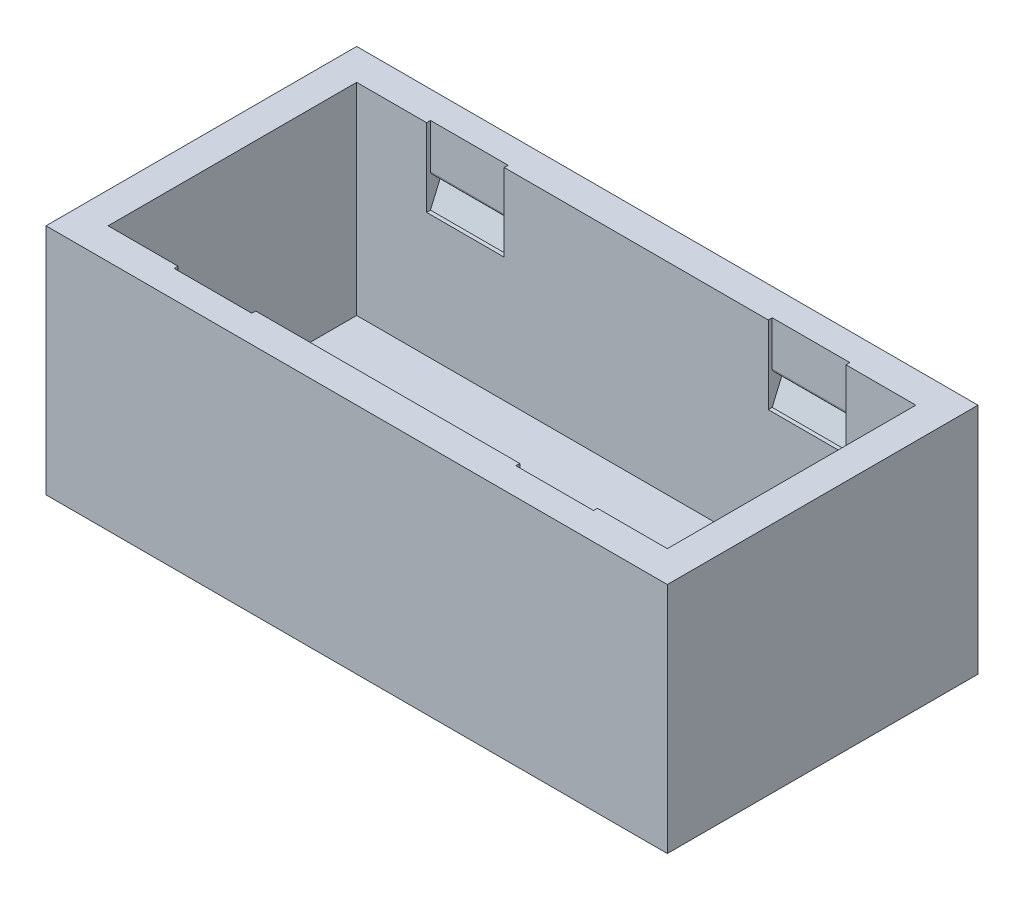
SolidWorks part; units mm, degrees
ref_plane "Front Plane" through (0, 0, 0) normal (0, 0, 1) x (1, 0, 0)
ref_plane "Top Plane" through (0, 0, 0) normal (0, 1, 0) x (1, 0, 0)
ref_plane "Right Plane" through (0, 0, 0) normal (1, 0, 0) x (0, 0, -1)
sketch "Sketch1" plane through (0, 0, 0) normal (0, 1, 0) x (1, 0, 0)
  line L1 (-20, 10) -> (20, 10)
  line L2 (-20, 10) -> (-20, -10)
  line L3 (-20, -10) -> (20, -10)
  line L4 (20, 10) -> (20, -10)
  line L5 (-20, 10) -> (20, -10) construction
  line L6 (-20, -10) -> (20, 10) construction
  point P0 (0, 0)
  dimension "D1" = 40
  dimension "D2" = 20
extrude "Boss-Extrude1" add sketch "Sketch1" along normal blind 15
shell "Shell2" thickness 2
sketch "Sketch2" plane through (0, 0, 0) normal (1, 0, 0) x (0, 0, -1)
  line L0 (8.25, 15) -> (8.25, 12.1442)
  line L1 (-10, 15) -> (10, 15) construction
  line L2 (8.3868, 11.9544) -> (9, 11.75)
  line L3 (9, 11.75) -> (8.25, 10)
  line L4 (8.25, 10) -> (7.25, 10)
  line L6 (7.25, 10) -> (7.25, 15)
  line L7 (7.25, 15) -> (8.25, 15)
  line L8 (8.25, 12) -> (8.25, 10) construction
  line L9 (10, 15) -> (10, 0) construction
  line L10 (8, 15) -> (8, 10)
  arc A0 (8.25, 12.1442) -> (8.3868, 11.9544) centre (8.45, 12.1442) ccw
  dimension "D7" = 0.2
  dimension "D1" = 3
  dimension "D2" = 5
  dimension "D3" = 1
  dimension "D4" = 1
  dimension "D5" = 0.25
  dimension "D6" = 1.75
extrude "Cut-Extrude1" cut sketch "Sketch2" against normal mid plane 5 from offset 11 contours L2 L8 L3 | L8 L0 L7 L10 L4 offset against normal yes
mirror "Mirror1" about plane through (0, 0, 0) normal (1, 0, 0) of "Cut-Extrude1"
mirror "Mirror2" about plane through (0, 0, 0) normal (0, 0, 1) of "Mirror1", "Cut-Extrude1"
